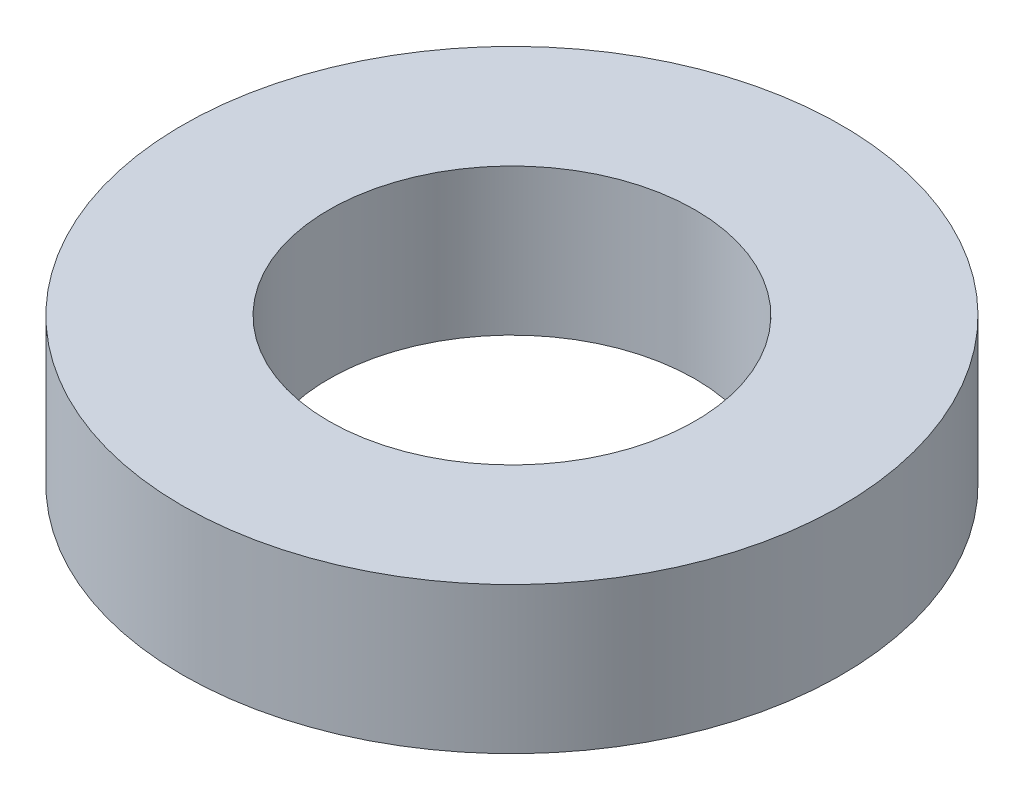
SolidWorks part; units mm, degrees
ref_plane "Front Plane" through (0, 0, 0) normal (0, 0, 1) x (1, 0, 0)
ref_plane "Top Plane" through (0, 0, 0) normal (0, 1, 0) x (1, 0, 0)
ref_plane "Right Plane" through (0, 0, 0) normal (1, 0, 0) x (0, 0, -1)
sketch "Sketch1" plane through (0, 0, 0) normal (0, 1, 0) x (1, 0, 0)
  circle A0 centre (0, 0) radius 15.875
  circle A1 centre (0, 0) radius 28.575
  dimension "D1" = 31.75
  dimension "D2" = 57.15
extrude "Boss-Extrude1" add sketch "Sketch1" along normal blind 12.7
